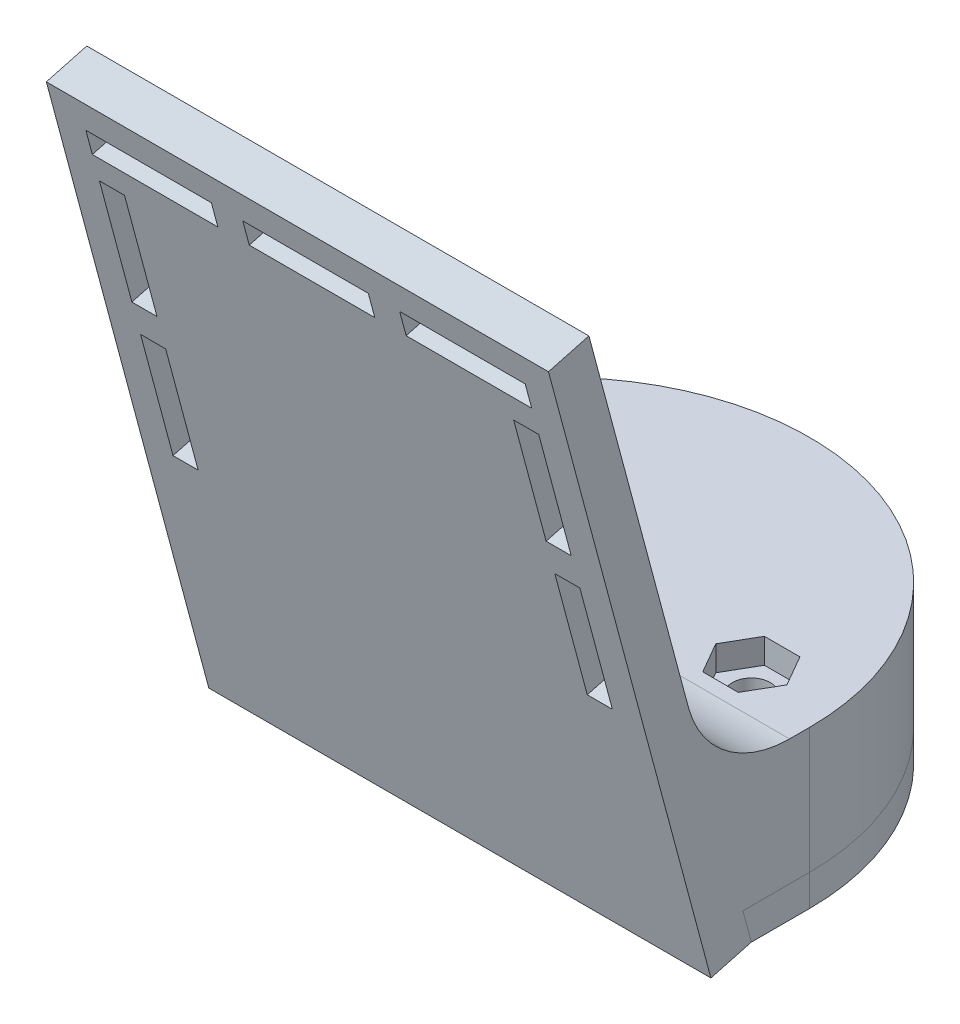
SolidWorks part; units mm, degrees
ref_plane "Front Plane" through (0, 0, 0) normal (0, 0, 1) x (1, 0, 0)
ref_plane "Top Plane" through (0, 0, 0) normal (0, 1, 0) x (1, 0, 0)
ref_plane "Right Plane" through (0, 0, 0) normal (1, 0, 0) x (0, 0, -1)
sketch "Sketch1" plane through (0, 0, 0) normal (0, 1, 0) x (1, 0, 0)
  line L1 (30, -6.046) -> (-30, -6.046)
  line L2 (30, -6.046) -> (30, 5.954)
  line L4 (-30, -6.046) -> (-30, 5.954)
  arc A2 (30, 5.954) -> (-30, 5.954) centre (0, 5.954) ccw
  circle A3 centre (0, 18.454) radius 7.5
  point P5 (0, 0)
  point P7 (0, 0)
  dimension "D3" = 30
  dimension "D5" = 12.5
  dimension "D4" = 15
  dimension "D1" = 60
  dimension "D2" = 12
extrude "Boss-Extrude1" add sketch "Sketch1" along normal blind 2
sketch "Sketch2" plane through (0, 2, 0) normal (0, 1, 0) x (1, 0, 0)
  line L9 (30, -6.046) -> (30, 5.954)
  line L10 (-30, 5.954) -> (-30, -6.046)
  line L11 (-30, -6.046) -> (30, -6.046)
  line L12 (30, -6.046) -> (30, 5.954)
  line L13 (-30, 5.954) -> (-30, -6.046)
  line L14 (-30, -6.046) -> (30, -6.046)
  circle A2 centre (0, 28.954) radius 2.25
  circle A11 centre (2.3872, 8.229) radius 2.25
  circle A14 centre (0, 18.454) radius 15.125
  circle A22 centre (0, 18.454) radius 10.5 construction
  circle A23 centre (0, 18.454) radius 7.5 construction
  arc A25 (30, 5.954) -> (-30, 5.954) centre (0, 5.954) ccw
  arc A26 (30, 5.954) -> (-30, 5.954) centre (0, 5.954) ccw
  point P2 (1.6304, 8.0814)
  point P6 (0, 16.4898)
  point P9 (-0.102, 16.3137)
  point P13 (3.4747, 6.0456)
  point P16 (2.3872, 8.229)
  point P29 (-1.4391, 19.4163)
  dimension "D3" = 30.25
  dimension "D5" = 4.5
  dimension "D2" = 21
  dimension "D1" = 0
extrude "Boss-Extrude2" add sketch "Sketch2" along normal blind 1.75
sketch "Sketch5" plane through (0, 3.75, 0) normal (0, 1, 0) x (1, 0, 0)
  line L7 (-30, -6.046) -> (30, -6.046)
  line L8 (30, -6.046) -> (30, 5.954)
  line L9 (-30, 5.954) -> (-30, -6.046)
  line L10 (-30, -6.046) -> (30, -6.046)
  line L11 (30, -6.046) -> (30, 5.954)
  line L12 (-30, 5.954) -> (-30, -6.046)
  arc A2 (30, 5.954) -> (-30, 5.954) centre (0, 5.954) ccw
  arc A3 (30, 5.954) -> (-30, 5.954) centre (0, 5.954) ccw
  dimension "D1" = 0
extrude "Boss-Extrude3" add sketch "Sketch5" along normal blind 15 separate body
sketch "Sketch6" plane through (-30, 0, 0) normal (-1, 0, 0) x (0, 0, 1)
  line L4 (6.046, 18.75) -> (6.046, 0)
  line L5 (6.046, 18.75) -> (1.0219, 0)
  line L6 (6.046, 0) -> (-5.954, 0) construction
  line L7 (1.0219, 0) -> (6.046, 0)
  point P5 (6.046, 20)
  dimension "D1" = 15
extrude "Cut-Extrude2" cut sketch "Sketch6" against normal blind 60
sketch "Sketch8" plane through (0, -0.2555, 0.9535) normal (0, -0.2588, 0.9659) x (1, 0, 0)
  line L0 (30, 0.2645) -> (-30, 0.2645) construction
  line L1 (-30, 0.2645) -> (30, 0.2645)
  line L2 (-30, 0.2645) -> (-30, 75.2645)
  line L3 (-30, 75.2645) -> (30, 75.2645)
  line L4 (30, 0.2645) -> (30, 75.2645)
  point P4 (24.998, 0.7499)
  point P5 (12.0609, 0.3084)
  point P6 (24.9223, 1.0514)
  point P9 (30, 0.7499)
  dimension "D1" = 75
  dimension "D2" = 60
extrude "Boss-Extrude4" add sketch "Sketch8" along normal blind 5
sketch "Sketch9" plane through (0, 0, 0) normal (0, -1, 0) x (1, 0, 0)
  line L0 (-30, 1.0219) -> (-30, -5.954) construction
  line L3 (30, 1.0219) -> (30, -5.954) construction
  line L5 (-30, 1.0219) -> (30, 1.0219) construction
  circle A0 centre (-20, -8.9781) radius 2.25
  circle A1 centre (20, -8.9781) radius 2.25
  dimension "D1" = 4.5
  dimension "D2" = 10
  dimension "6mm" = 10
  dimension "D3" = 10
extrude "Cut-Extrude4" cut sketch "Sketch9" against normal blind 20
sketch "Sketch10" plane through (0, -0.2555, 0.9535) normal (0, 0.2588, -0.9659) x (-1, 0, 0)
  line L0 (-30, 19.6759) -> (-30, 75.2645) construction
  line L1 (-26.25, 71.5145) -> (-11.25, 71.5145)
  line L2 (-26.25, 71.5145) -> (-26.25, 68.5145)
  line L3 (-26.25, 68.5145) -> (-11.25, 68.5145)
  line L4 (-11.25, 71.5145) -> (-11.25, 68.5145)
  line L9 (-7.5, 71.5145) -> (7.5, 71.5145)
  line L10 (-7.5, 71.5145) -> (-7.5, 68.5145)
  line L11 (-7.5, 68.5145) -> (7.5, 68.5145)
  line L12 (7.5, 71.5145) -> (7.5, 68.5145)
  line L13 (11.25, 71.5145) -> (26.25, 71.5145)
  line L14 (11.25, 71.5145) -> (11.25, 68.5145)
  line L15 (11.25, 68.5145) -> (26.25, 68.5145)
  line L16 (26.25, 71.5145) -> (26.25, 68.5145)
  line L17 (-30, 75.2645) -> (30, 75.2645) construction
  line L18 (-26.25, 46.2645) -> (-23.25, 46.2645)
  line L19 (-26.25, 65.2645) -> (-23.25, 65.2645)
  line L20 (-26.25, 65.2645) -> (-26.25, 50.2645)
  line L21 (-26.25, 50.2645) -> (-23.25, 50.2645)
  line L22 (-23.25, 65.2645) -> (-23.25, 50.2645)
  line L23 (-23.25, 46.2645) -> (-23.25, 31.2645)
  line L24 (-26.25, 46.2645) -> (-26.25, 31.2645)
  line L25 (-26.25, 31.2645) -> (-23.25, 31.2645)
  line L26 (0, 2.0625) -> (0, -2.0625) construction
  line L27 (26.25, 31.2645) -> (23.25, 31.2645)
  line L28 (26.25, 46.2645) -> (26.25, 31.2645)
  line L29 (23.25, 46.2645) -> (23.25, 31.2645)
  line L30 (23.25, 65.2645) -> (23.25, 50.2645)
  line L31 (26.25, 50.2645) -> (23.25, 50.2645)
  line L32 (26.25, 65.2645) -> (26.25, 50.2645)
  line L33 (26.25, 65.2645) -> (23.25, 65.2645)
  line L34 (26.25, 46.2645) -> (23.25, 46.2645)
  dimension "D1" = 15
  dimension "D2" = 3.75
  dimension "D4" = 3
  dimension "D5" = 3.75
  dimension "D6" = 3
  dimension "D7" = 15
  dimension "D8" = 3.75
  dimension "D9" = 10
  dimension "D11" = 4
  dimension "D3" = 3
  dimension "D10" = 2
extrude "Cut-Extrude5" cut sketch "Sketch10" against normal blind 25
sketch "Sketch11" plane through (0, 18.75, 0) normal (0, 1, 0) x (1, 0, 0)
  line L1 (-17.875, 12.6587) -> (-22.125, 12.6587)
  line L2 (-22.125, 12.6587) -> (-24.25, 8.9781)
  line L3 (-24.25, 8.9781) -> (-22.125, 5.2975)
  line L4 (-22.125, 5.2975) -> (-17.875, 5.2975)
  line L5 (-17.875, 5.2975) -> (-15.75, 8.9781)
  line L6 (-15.75, 8.9781) -> (-17.875, 12.6587)
  line L7 (22.125, 12.6587) -> (17.875, 12.6587)
  line L8 (17.875, 12.6587) -> (15.75, 8.9781)
  line L9 (15.75, 8.9781) -> (17.875, 5.2975)
  line L10 (17.875, 5.2975) -> (22.125, 5.2975)
  line L11 (22.125, 5.2975) -> (24.25, 8.9781)
  line L12 (24.25, 8.9781) -> (22.125, 12.6587)
  circle A0 centre (-20, 8.9781) radius 3.6806 construction
  circle A1 centre (20, 8.9781) radius 3.6806 construction
  dimension "D1" = 4.25
extrude "Cut-Extrude6" cut sketch "Sketch11" against normal blind 3
fillet "Fillet1" radius 12.5 1 edges at (0, 18.75, 6.046)
